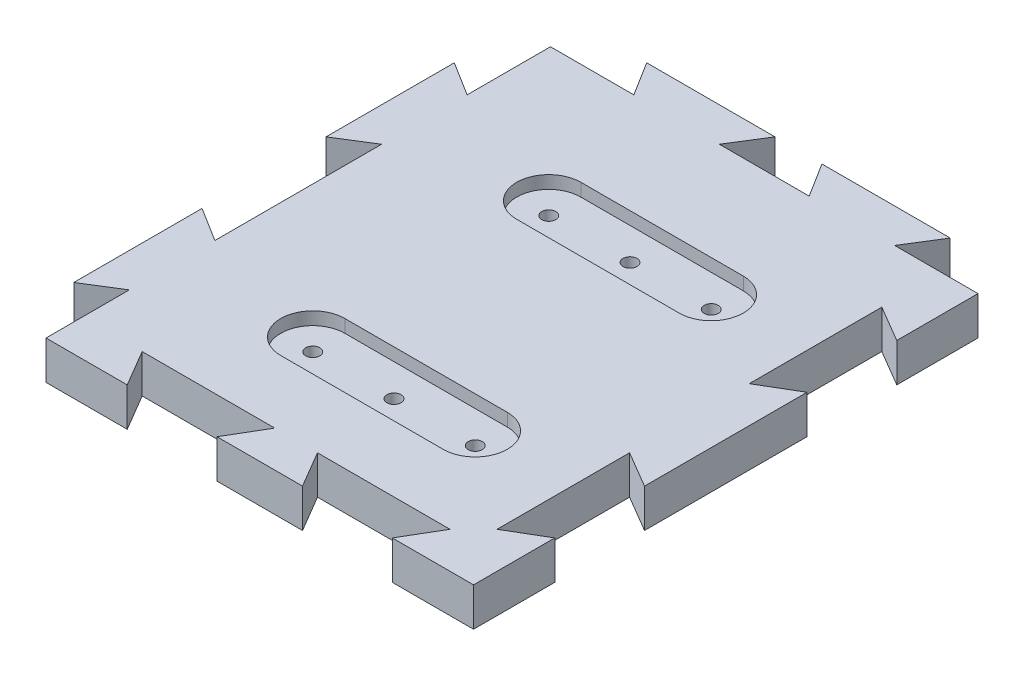
SolidWorks part; units mm, degrees
ref_plane "Front Plane" through (0, 0, 0) normal (0, 0, 1) x (1, 0, 0)
ref_plane "Top Plane" through (0, 0, 0) normal (0, 1, 0) x (1, 0, 0)
ref_plane "Right Plane" through (0, 0, 0) normal (1, 0, 0) x (0, 0, -1)
sketch "Sketch2" plane through (0, 0, 0) normal (0, 1, 0) x (1, 0, 0)
  line L0 (0, 98.5) -> (-8, 103.5)
  line L1 (0, 0) -> (19, 0)
  line L2 (0, 0) -> (0, 19.5)
  line L3 (0, 118) -> (19.5, 118)
  line L4 (100, 0) -> (100, 19)
  line L5 (-8, 103.5) -> (-8, 73.5)
  line L6 (-8, 73.5) -> (0, 78.5)
  line L8 (19, 0) -> (14, 8.5)
  line L10 (-8, 44.5) -> (0, 39.5)
  line L11 (-8, 14.5) -> (-8, 44.5)
  line L12 (0, 19.5) -> (-8, 14.5)
  line L13 (0, 98.5) -> (0, 118)
  line L14 (0, 39.5) -> (0, 78.5)
  line L15 (100, 99) -> (91.5, 104)
  line L16 (91.5, 104) -> (91.5, 73)
  line L17 (91.5, 73) -> (100, 78)
  line L19 (100, 99) -> (100, 118)
  line L20 (100, 19) -> (91.5, 14)
  line L21 (91.5, 45) -> (100, 40)
  line L22 (91.5, 14) -> (91.5, 45)
  line L23 (100, 40) -> (100, 78)
  line L24 (19.5, 118) -> (14.5, 126)
  line L25 (14.5, 126) -> (44.5, 126)
  line L26 (44.5, 126) -> (39.5, 118)
  line L27 (39.5, 118) -> (60.5, 118)
  line L29 (55.5, 126) -> (60.5, 118)
  line L30 (85.5, 126) -> (55.5, 126)
  line L31 (80.5, 118) -> (85.5, 126)
  line L32 (80.5, 118) -> (100, 118)
  line L33 (81, 0) -> (86, 8.5)
  line L34 (86, 8.5) -> (55, 8.5)
  line L35 (55, 8.5) -> (60, 0)
  line L36 (14, 8.5) -> (45, 8.5)
  line L37 (45, 8.5) -> (40, 0)
  line L38 (40, 0) -> (60, 0)
  line L39 (81, 0) -> (100, 0)
  circle A0 centre (31, 31.4) radius 1.65
  circle A1 centre (31, 86.6) radius 1.65
  circle A2 centre (50, 31.4) radius 1.65
  circle A3 centre (50, 86.6) radius 1.65
  circle A4 centre (69, 31.4) radius 1.65
  circle A5 centre (69, 86.6) radius 1.65
  point P42 (50, 0)
  dimension "D1" = 3.3
  dimension "D2" = 3.3
  dimension "D3" = 3.3
  dimension "D4" = 3.3
  dimension "D5" = 3.3
  dimension "D18" = 3.3
  dimension "D30" = 19
  dimension "D6" = 100
  dimension "D7" = 19.5
  dimension "D8" = 19
  dimension "D9" = 19
  dimension "D10" = 31
  dimension "D11" = 55.2
  dimension "D12" = 31.4
  dimension "D13" = 20
  dimension "D14" = 30
  dimension "D15" = 5
  dimension "D16" = 8
  dimension "D17" = 19.5
  dimension "D19" = 8.5
  dimension "D20" = 19
  dimension "D21" = 31
  dimension "D22" = 21
  dimension "D23" = 5
  dimension "D24" = 5
  dimension "D25" = 20
  dimension "D26" = 21
  dimension "D27" = 30
  dimension "D28" = 118
  dimension "D29" = 8
  dimension "D31" = 5
  dimension "D32" = 31
  dimension "D33" = 21
  dimension "D34" = 8.5
  dimension "D35" = 19.5
  dimension "D36" = 30
  dimension "D37" = 20
  dimension "D38" = 5
  dimension "D39" = 8
  dimension "D40" = 19
  dimension "D41" = 31
  dimension "D42" = 5
  dimension "D43" = 8.5
  dimension "D44" = 19
  dimension "D45" = 21
  dimension "D46" = 31
  dimension "D47" = 8.5
  dimension "D48" = 5
  dimension "D49" = 19.5
  dimension "D50" = 30
  dimension "D51" = 20
  dimension "D52" = 5
  dimension "D53" = 8
  dimension "D54" = 11
extrude "Boss-Extrude2" add sketch "Sketch2" along normal blind 9
sketch "Sketch4" plane through (0, 9, 0) normal (0, 1, 0) x (1, 0, 0)
  line L0 (31, 94.1) -> (69, 94.1)
  line L1 (31, 79.1) -> (69, 79.1)
  line L2 (31, 38.9) -> (69, 38.9)
  line L3 (31, 23.9) -> (69, 23.9)
  arc A0 (31, 94.1) -> (31, 79.1) centre (31, 86.6) ccw
  arc A2 (69, 79.1) -> (69, 94.1) centre (69, 86.6) ccw
  arc A3 (31, 38.9) -> (31, 23.9) centre (31, 31.4) ccw
  arc A5 (69, 23.9) -> (69, 38.9) centre (69, 31.4) ccw
  dimension "D1" = 15
  dimension "D2" = 15
  dimension "D3" = 15
  dimension "D4" = 15
extrude "Cut-Extrude1" cut sketch "Sketch4" against normal blind 3
